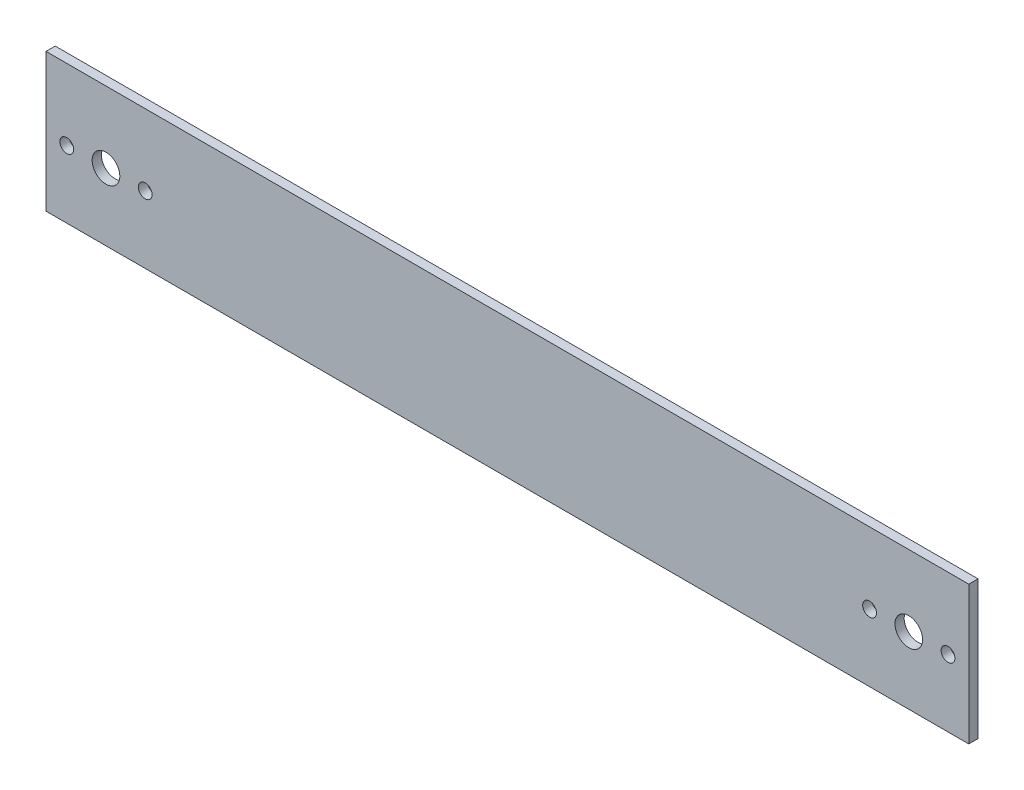
SolidWorks part; units mm, degrees
ref_plane "Front Plane" through (0, 0, 0) normal (0, 0, 1) x (1, 0, 0)
ref_plane "Top Plane" through (0, 0, 0) normal (0, 1, 0) x (1, 0, 0)
ref_plane "Right Plane" through (0, 0, 0) normal (1, 0, 0) x (0, 0, -1)
sketch "Sketch1" plane through (0, 0, 0) normal (0, 0, 1) x (1, 0, 0)
  line L0 (-77.4629, 35.6275) -> (22.5371, 35.6275)
  line L1 (22.5371, 35.6275) -> (22.5371, 5.6275)
  line L2 (22.5371, 5.6275) -> (-77.4629, 5.6275)
  line L3 (-77.4629, 5.6275) -> (-77.4629, 35.6275)
  dimension "D1" = 100
  dimension "D2" = 30
extrude "Boss-Extrude1" add sketch "Sketch1" along normal blind 2
sketch "Sketch2" plane through (0, 0, 2) normal (0, 0, 1) x (1, 0, 0)
  line L0 (-77.4629, 35.6275) -> (-77.4629, 5.6275) construction
  circle A0 centre (-64.4629, 20.197) radius 3
  circle A1 centre (-72.9629, 20.197) radius 1.5
  circle A2 centre (-55.9629, 20.197) radius 1.5
  point P8 (0, 0)
  dimension "D1" = 8.5
  dimension "D2" = 8.5
extrude "Cut-Extrude2" cut sketch "Sketch2" against normal blind 2
mirror "Mirror2" about plane through (22.5371, 35.6275, 2) normal (-1, 0, 0) of "Boss-Extrude1", "Cut-Extrude2"
